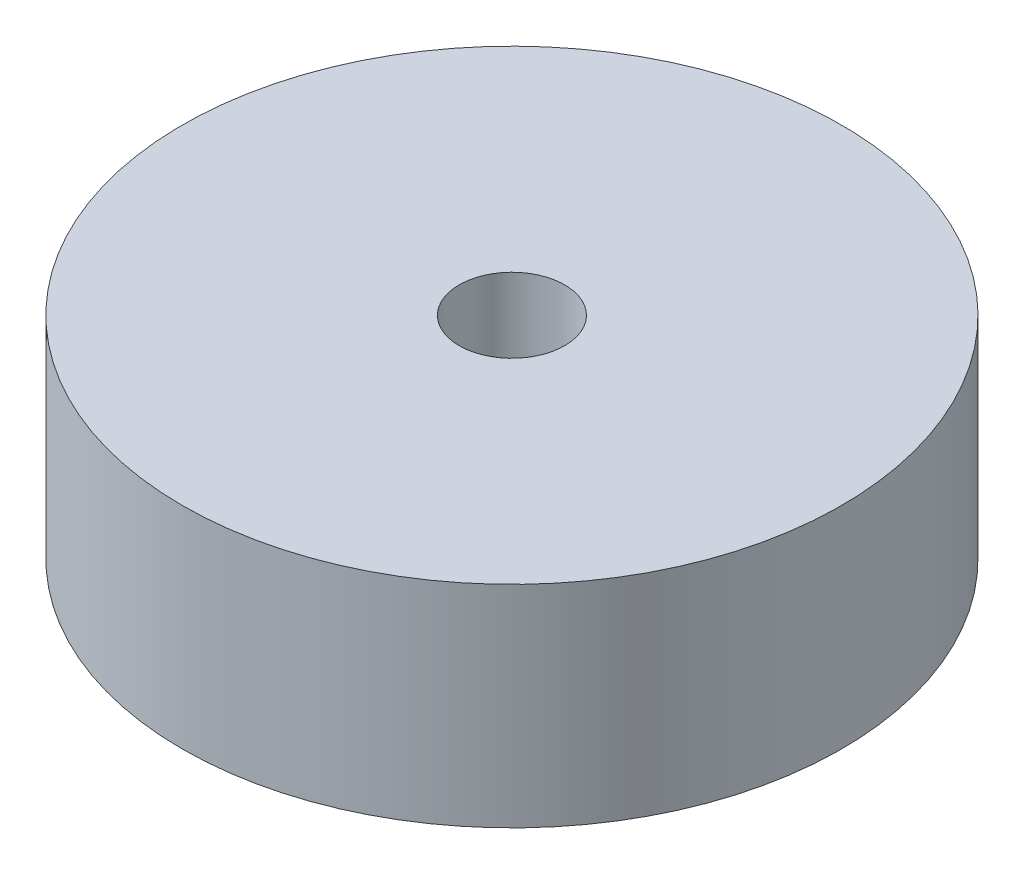
SolidWorks part; units mm, degrees
ref_plane "Front Plane" through (0, 0, 0) normal (0, 0, 1) x (1, 0, 0)
ref_plane "Top Plane" through (0, 0, 0) normal (0, 1, 0) x (1, 0, 0)
ref_plane "Right Plane" through (0, 0, 0) normal (1, 0, 0) x (0, 0, -1)
sketch "Sketch1" plane through (0, 0, 0) normal (0, 1, 0) x (1, 0, 0)
  circle A0 centre (0, 0) radius 4
  circle A1 centre (0, 0) radius 25
  dimension "D1" = 8
  dimension "D2" = 50
extrude "Boss-Extrude1" add sketch "Sketch1" along normal blind 16
